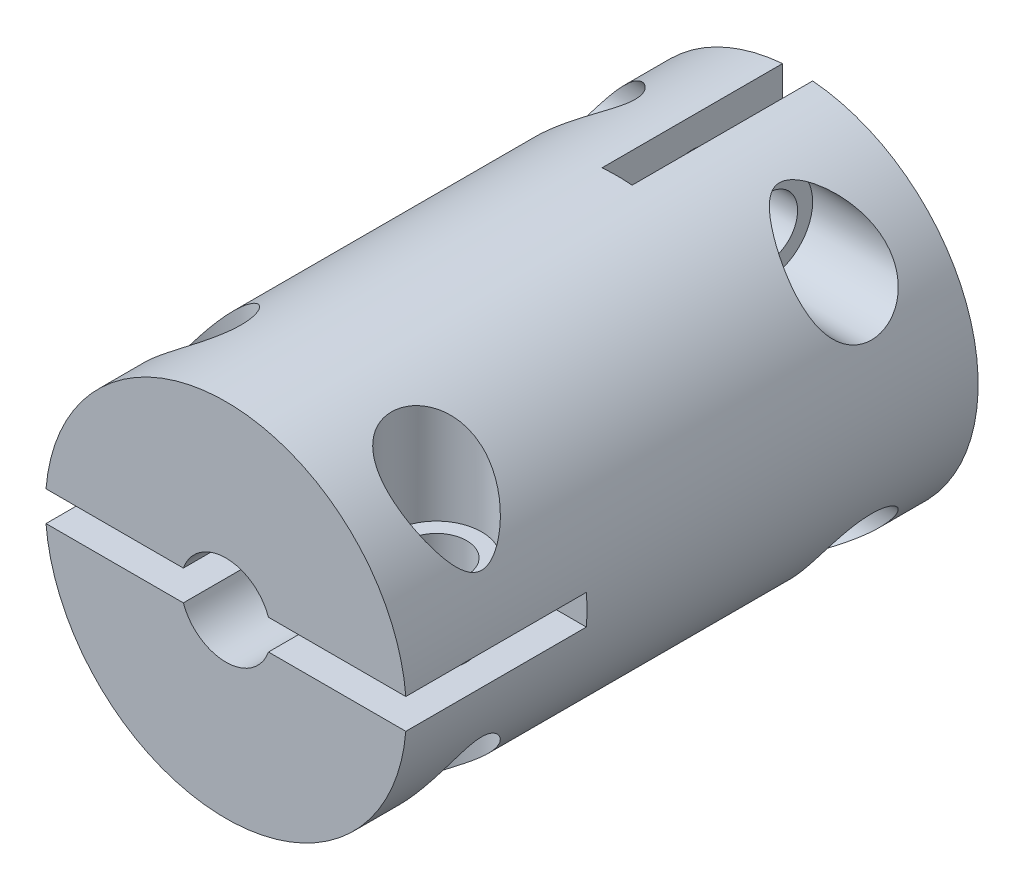
SolidWorks part; units mm, degrees
ref_plane "前视基准面" through (0, 0, 0) normal (0, 0, 1) x (1, 0, 0)
ref_plane "上视基准面" through (0, 0, 0) normal (0, 1, 0) x (1, 0, 0)
ref_plane "右视基准面" through (0, 0, 0) normal (1, 0, 0) x (0, 0, -1)
sketch "草图1" plane through (0, 0, 0) normal (0, 0, 1) x (1, 0, 0)
  circle A0 centre (0, 0) radius 6
  dimension "D1" = 12
extrude "凸台-拉伸1" add sketch "草图1" along normal blind 19
sketch "草图2" plane through (0, 0, 19) normal (0, 0, 1) x (1, 0, 0)
  circle A0 centre (0, 0) radius 1.5
  dimension "D1" = 3
extrude "切除-拉伸1" cut sketch "草图2" against normal blind 9.5
sketch "草图3" plane through (0, 0, 19) normal (0, 0, 1) x (1, 0, 0)
  line L0 (-7.588, 0) -> (6.7739, 0) construction
  line L2 (-7.0045, 0.5) -> (6.6233, 0.5)
  line L3 (-7.0045, 0.5) -> (-7.0045, -0.5)
  line L4 (-7.0045, -0.5) -> (6.6233, -0.5)
  line L5 (6.6233, 0.5) -> (6.6233, -0.5)
  dimension "D1" = 1
  dimension "D2" = 0.5
extrude "切除-拉伸2" cut sketch "草图3" against normal blind 6
sketch "草图4" plane through (0, 0, 0) normal (0, 0, -1) x (-1, 0, 0)
  line L0 (0, 6.68) -> (0, -6.9403) construction
  line L2 (-0.5, 6.2896) -> (0.5, 6.2896)
  line L3 (-0.5, 6.2896) -> (-0.5, -6.5065)
  line L4 (-0.5, -6.5065) -> (0.5, -6.5065)
  line L5 (0.5, 6.2896) -> (0.5, -6.5065)
  dimension "D1" = 1
  dimension "D2" = 0.5
extrude "切除-拉伸3" cut sketch "草图4" against normal blind 6
sketch "草图5" plane through (0, 0, 0) normal (0, 1, 0) x (1, 0, 0)
  line L0 (0, 0) -> (0, -20.2214) construction
  line L1 (-5.9791, -19) -> (5.9791, -19) construction
  circle A0 centre (-4, -16) radius 1
  circle A1 centre (4, -16) radius 1
  dimension "D1" = 2
  dimension "D2" = 2
  dimension "D5" = 3
  dimension "D6" = 3
  dimension "D3" = 8
  dimension "D4" = 4
extrude "切除-拉伸5" cut sketch "草图5" against normal blind 6 and the other way blind 6
sketch "草图6" plane through (0, 0, 0) normal (0, 1, 0) x (1, 0, 0)
  circle A0 centre (-4, -16) radius 1.5
  circle A1 centre (4, -16) radius 1.5
  dimension "D1" = 3
  dimension "D2" = 3
extrude "切除-拉伸6" cut sketch "草图6" against normal blind 6 from offset 2 offset against normal yes
mirror "镜向1" about plane through (0, 0, 0) normal (0, 1, 0) of "切除-拉伸6"
sketch "草图7" plane through (0, 0, 0) normal (1, 0, 0) x (0, 0, -1)
  line L0 (0, -5.9791) -> (0, 5.9791) construction
  circle A0 centre (-3, 4) radius 1
  circle A1 centre (-3, -4) radius 1
  dimension "D2" = 4
  dimension "D3" = 2
  dimension "D4" = 2
  dimension "D5" = 3
  dimension "D6" = 3
  dimension "D1" = 8
extrude "切除-拉伸7" cut sketch "草图7" against normal blind 6
sketch "草图8" plane through (0, 0, 0) normal (1, 0, 0) x (0, 0, -1)
  circle A0 centre (-3, -4) radius 1.5
  circle A1 centre (-3, 4) radius 1.5
  dimension "D1" = 3
  dimension "D2" = 3
extrude "切除-拉伸8" cut sketch "草图8" against normal blind 6 from offset 2 offset against normal yes
mirror "镜向2" about plane through (0, 0, 0) normal (1, 0, 0) of "切除-拉伸7", "切除-拉伸8"
sketch "草图9" plane through (0, 0, 0) normal (0, 0, -1) x (-1, 0, 0)
  circle A0 centre (0, 0) radius 2
  dimension "D1" = 4
extrude "切除-拉伸9" cut sketch "草图9" against normal blind 9.5
